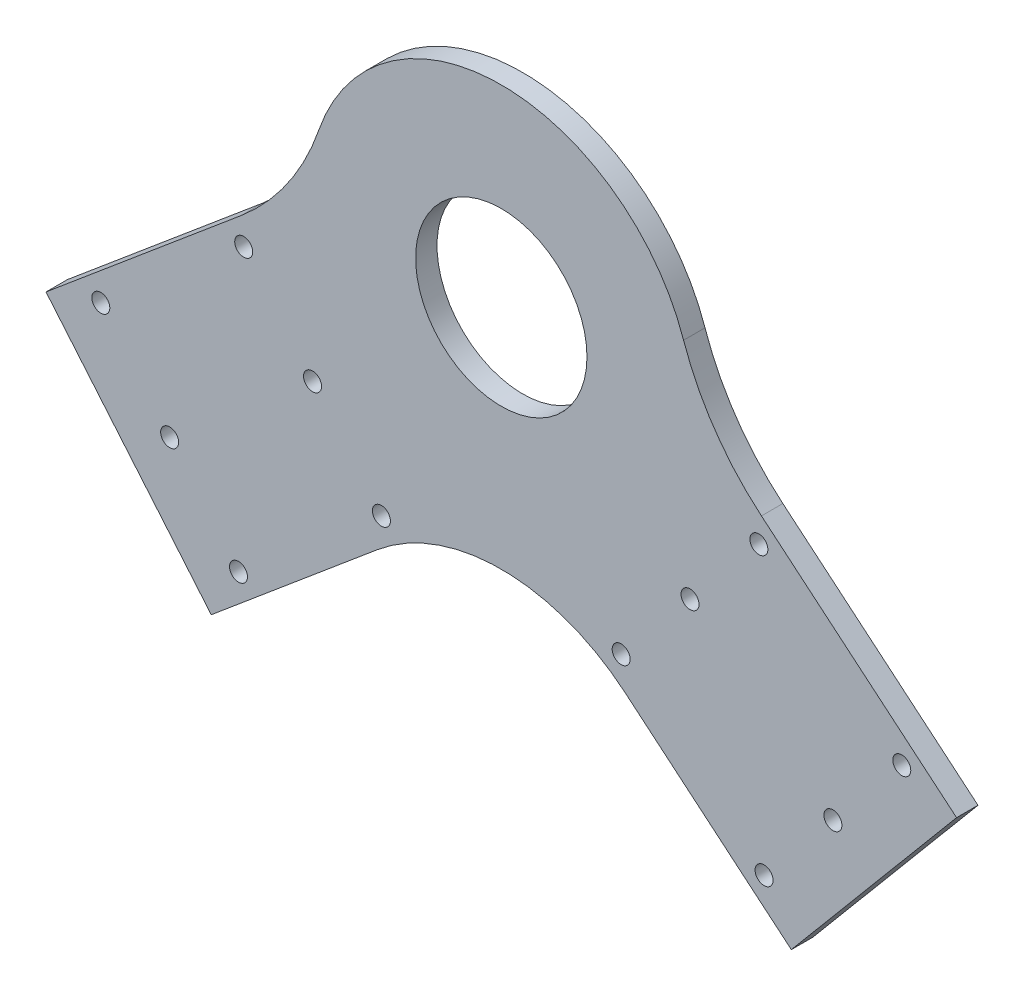
SolidWorks part; units mm, degrees
ref_plane "Front Plane" through (0, 0, 0) normal (0, 0, 1) x (1, 0, 0)
ref_plane "Top Plane" through (0, 0, 0) normal (0, 1, 0) x (1, 0, 0)
ref_plane "Right Plane" through (0, 0, 0) normal (1, 0, 0) x (0, 0, -1)
sketch "Sketch1" plane through (0, 0, 0) normal (0, 0, 1) x (1, 0, 0)
  line L0 (0, 0) -> (0, 50000) construction
  line L1 (0, 0) -> (50000, 0) construction
  line L2 (0, 0) -> (-1203.5328, -1009.8839) construction
  line L3 (-67.6938, -95.9641) -> (-6.4103, -44.5411)
  line L4 (-67.6938, -95.9641) -> (-106.2611, -50.0014)
  line L6 (-106.2611, -50.0014) -> (-44.9775, 1.4216)
  line L7 (67.6938, -95.9641) -> (106.2611, -50.0014)
  line L8 (106.2611, -50.0014) -> (44.9775, 1.4216)
  line L9 (67.6938, -95.9641) -> (6.4103, -44.5411)
  line L10 (-6.4103, -44.5411) -> (0, -39.1622)
  line L11 (6.4103, -44.5411) -> (0, -39.1622)
  line L12 (96.6855, -41.9666) -> (58.1183, -87.9292) construction
  line L13 (63.332, -13.9796) -> (24.7647, -59.9423) construction
  arc A0 (6.4103, -44.5411) -> (-6.4103, -44.5411) centre (0, 0) ccw
  circle A1 centre (0, 0) radius 20
  circle A2 centre (93.4716, -45.7968) radius 2.1
  circle A3 centre (77.4019, -64.9479) radius 2.1
  circle A4 centre (61.3322, -84.099) radius 2.1
  circle A5 centre (-61.3322, -84.099) radius 2.1
  circle A6 centre (-77.4019, -64.9479) radius 2.1
  circle A7 centre (-93.4716, -45.7968) radius 2.1
  circle A8 centre (60.118, -17.8098) radius 2.1
  circle A9 centre (44.0483, -36.9609) radius 2.1
  circle A10 centre (27.9786, -56.1121) radius 2.1
  circle A11 centre (-27.9786, -56.1121) radius 2.1
  circle A12 centre (-44.0483, -36.9609) radius 2.1
  circle A13 centre (-60.118, -17.8098) radius 2.1
  dimension "D1" = 90
  dimension "D2" = 50
  dimension "D6" = 40
  dimension "D8" = 4.2
  dimension "D3" = 30
  dimension "D4" = 30
  dimension "D5" = 80
  dimension "D7" = 12.5
  dimension "D9" = 5
  dimension "D10" = 5
  dimension "D11" = 43.54
  dimension "D12" = 5
  dimension "D13" = 5
extrude "Boss-Extrude1" add sketch "Sketch1" along normal blind 5 contours A0 | A0 L6 L4 L3 L9 | A0 L3 L9 L7 L8 | A0 L9 L3
fillet "Fillet1" radius 60 2 edges at (44.9775, 1.4216, 2.5) (-44.9775, 1.4216, 2.5)
fillet "Fillet3" radius 45 1 edges at (0, -39.1622, 2.5)
